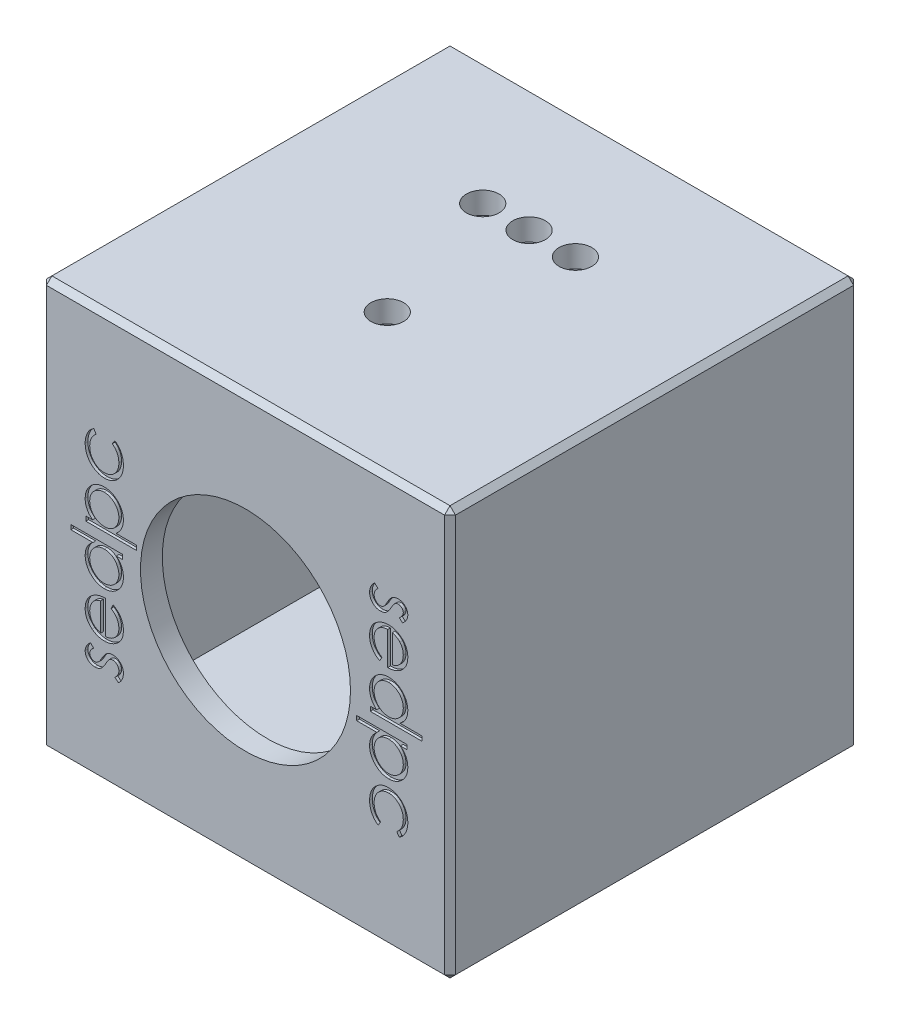
SolidWorks part; units mm, degrees
ref_plane "Alzado" through (0, 0, 0) normal (0, 0, 1) x (1, 0, 0)
ref_plane "Planta" through (0, 0, 0) normal (0, 1, 0) x (1, 0, 0)
ref_plane "Vista lateral" through (0, 0, 0) normal (1, 0, 0) x (0, 0, -1)
sketch "Croquis1" plane through (0, 0, 0) normal (0, 0, 1) x (1, 0, 0)
  line L0 (-670, 670) -> (-670, -670)
  line L1 (-750, -750) -> (750, -750)
  line L2 (-750, -750) -> (-750, 750)
  line L3 (-750, 750) -> (750, 750)
  line L4 (750, -750) -> (750, 750)
  line L5 (-670, 670) -> (670, 670)
  line L6 (670, 670) -> (670, -670)
  line L7 (670, -670) -> (-670, -670)
  point P0 (0, 0)
  dimension "D1" = 1500
  dimension "D2" = 1500
  dimension "D3" = 80
  dimension "D4" = 80
  dimension "D5" = 80
  dimension "D6" = 80
extrude "Saliente-Extruir2" add sketch "Croquis1" along normal blind 1420
sketch "Croquis2" plane through (0, 0, 0) normal (0, 0, -1) x (-1, 0, 0)
  line L0 (-750, 750) -> (750, 750)
  line L1 (750, 750) -> (750, -750)
  line L2 (750, -750) -> (-750, -750)
  line L3 (-750, -750) -> (-750, 750)
extrude "Saliente-Extruir3" add sketch "Croquis2" against normal blind 80
sketch "Croquis3" plane through (0, 0, 0) normal (0, 0, -1) x (-1, 0, 0)
  line L1 (-750, -750) -> (-750, 750) construction
  line L2 (-150, 150) -> (150, 150)
  line L3 (-150, -150) -> (150, -150)
  line L4 (750, -750) -> (-750, -750) construction
  line L5 (-150, 150) -> (-150, -150)
  line L7 (150, 150) -> (150, -150)
  line L8 (750, 750) -> (750, -750) construction
  dimension "D2" = 600
  dimension "D3" = 600
  dimension "D4" = 600
extrude "Cortar-Extruir1" cut sketch "Croquis3" against normal blind 80
sketch "Croquis4" plane through (0, 0, 1420) normal (0, 0, 1) x (1, 0, 0)
  line L0 (-750, 750) -> (750, 750)
  line L1 (750, 750) -> (750, -750)
  line L2 (750, -750) -> (-750, -750)
  line L3 (-750, -750) -> (-750, 750)
  circle A0 centre (0, 0) radius 385
  dimension "D1" = 770
extrude "Saliente-Extruir4" add sketch "Croquis4" along normal blind 80
sketch "Croquis5" plane through (0, -750, 0) normal (0, -1, 0) x (1, 0, 0)
  circle A0 centre (0, 460) radius 60
  circle A1 centre (-170, 460) radius 60
  circle A2 centre (170, 460) radius 60
  circle A3 centre (0, 980) radius 60
  dimension "D11" = 120
  dimension "D12" = 120
  dimension "D13" = 120
  dimension "D14" = 120
extrude "Cortar-Extruir2" cut sketch "Croquis5" against normal up to surface (1500 mm away) up to face at (0, 750, 750)
chamfer "Chaflán1" distance 20 angle 45 12 edges at (-750, 0, 1500) (-750, 750, 750) (0, 750, 1500) (750, 750, 750) (750, 0, 1500) (750, -750, 750) (0, -750, 1500) (-750, -750, 750) (-750, 0, 0) (0, 750, 0) (750, 0, 0) (0, -750, 0)
sketch "Croquis6" plane through (0, 0, 1500) normal (0, 0, 1) x (1, 0, 0)
  line L0 (-450.1695, -407.5219) -> (-450.1695, 382.2492) construction
  line L1 (0, 730) -> (0, -811.8846) construction
  line L2 (730, 730) -> (-730, 730) construction
  line L3 (450.1695, -407.5219) -> (450.1695, 382.2492) construction
  text T0 "sedpc" font "Century Gothic" height in points 700
extrude "Cortar-Extruir3" cut sketch "Croquis6" against normal blind 10
sketch "Croquis7" plane through (0, 0, 1500) normal (0, 0, 1) x (1, 0, 0)
  line L0 (457.5427, 393.3485) -> (457.5427, -415.5611) construction
  text T0 "sedpc" font "Century Gothic" height in points 700
extrude "Cortar-Extruir4" cut sketch "Croquis7" against normal blind 10
